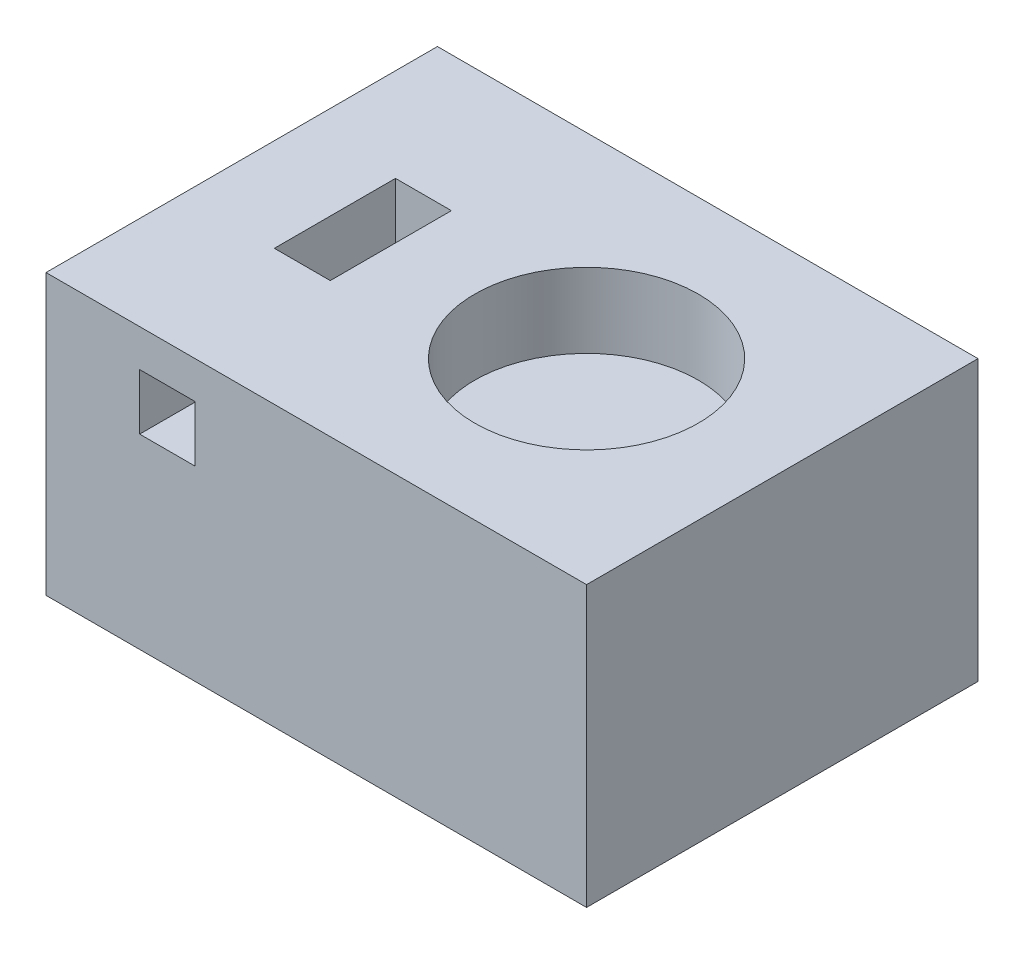
SolidWorks part; units mm, degrees
ref_plane "Plan de face" through (0, 0, 0) normal (0, 0, 1) x (1, 0, 0)
ref_plane "Plan de dessus" through (0, 0, 0) normal (0, 1, 0) x (1, 0, 0)
ref_plane "Plan de droite" through (0, 0, 0) normal (1, 0, 0) x (0, 0, -1)
sketch "Esquisse1" plane through (0, 0, 0) normal (0, 1, 0) x (1, 0, 0)
  line L1 (-21, 21) -> (21, 21)
  line L2 (-21, 21) -> (-21, -21)
  line L3 (-21, -21) -> (21, -21)
  line L4 (21, 21) -> (21, -21)
  line L5 (-21, 21) -> (21, -21) construction
  line L6 (-21, -21) -> (21, 21) construction
  point P0 (0, 0)
  dimension "D1" = 42
  dimension "D2" = 42
extrude "Boss.-Extru.1" add sketch "Esquisse1" along normal blind 30
sketch "Esquisse2" plane through (0, 30, 0) normal (0, 1, 0) x (1, 0, 0)
  circle A0 centre (0, 0) radius 12
  dimension "D1" = 24
extrude "Enlèv. mat.-Extru.1" cut sketch "Esquisse2" against normal blind 8
sketch "Esquisse3" plane through (0, 0, 21) normal (0, 0, 1) x (1, 0, 0)
  line L0 (21, 30) -> (21, 0) construction
  line L1 (-21, 30) -> (21, 30)
  line L2 (-21, 30) -> (-21, 0)
  line L3 (-21, 0) -> (21, 0)
  line L4 (21, 30) -> (21, 0)
sketch "Esquisse4" plane through (-21, 0, 0) normal (-1, 0, 0) x (0, 0, 1)
  line L0 (21, 30) -> (21, 0) construction
  line L1 (-21, 30) -> (21, 30)
  line L2 (-21, 30) -> (-21, 0)
  line L3 (-21, 0) -> (21, 0)
  line L4 (21, 30) -> (21, 0)
  line L5 (-21, 0) -> (21, 0) construction
extrude "Boss.-Extru.3" add sketch "Esquisse4" along normal blind 16
sketch "Esquisse5" plane through (0, 30, 0) normal (0, 1, 0) x (1, 0, 0)
  line L1 (-27, 6.5) -> (-21, 6.5)
  line L2 (-27, 6.5) -> (-27, -6.5)
  line L3 (-27, -6.5) -> (-21, -6.5)
  line L4 (-21, 6.5) -> (-21, -6.5)
  line L5 (21, 21) -> (-37, 21) construction
  line L7 (-37, -21) -> (-37, 21) construction
  dimension "D1" = 13
  dimension "D2" = 6
  dimension "D3" = 14.5
  dimension "D4" = 10
extrude "Enlèv. mat.-Extru.2" cut sketch "Esquisse5" against normal blind 11
sketch "Esquisse6" plane through (0, 0, -6.5) normal (0, 0, 1) x (1, 0, 0)
  line L0 (-21, 30) -> (-21, 0) construction
  line L1 (-26.9494, 20.0092) -> (-21, 20.0092)
  line L2 (-26.9494, 20.0092) -> (-26.9494, 26.0092)
  line L3 (-26.9494, 26.0092) -> (-21, 26.0092)
  line L4 (-21, 20.0092) -> (-21, 26.0092)
  dimension "D1" = 6
extrude "Enlèv. mat.-Extru.3" cut sketch "Esquisse6" along normal through all
